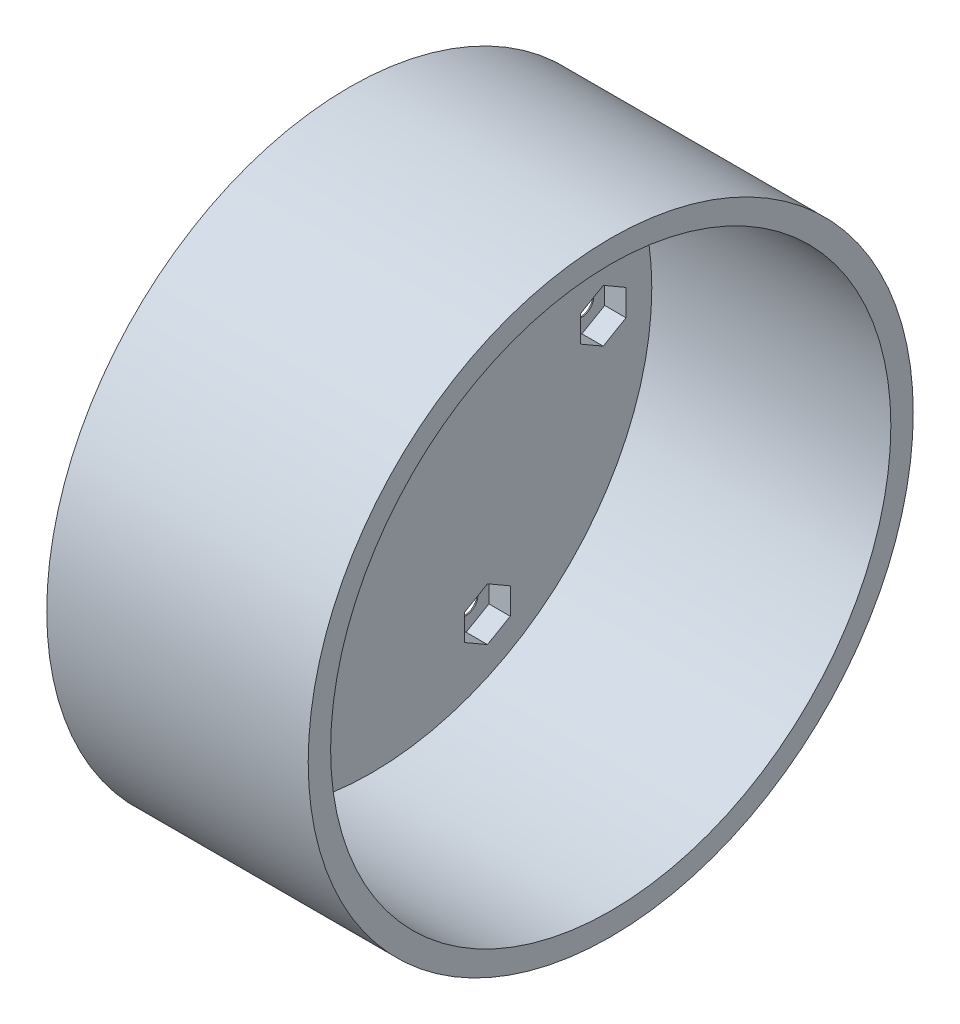
SolidWorks part; units mm, degrees
ref_plane "Front Plane" through (0, 0, 0) normal (0, 0, 1) x (1, 0, 0)
ref_plane "Top Plane" through (0, 0, 0) normal (0, 1, 0) x (1, 0, 0)
ref_plane "Right Plane" through (0, 0, 0) normal (1, 0, 0) x (0, 0, -1)
sketch "Sketch1" plane through (0, 0, 0) normal (0, 0, 1) x (1, 0, 0)
  line L0 (0, 0) -> (84.887, 0) construction
  line L7 (0, 0) -> (0, 40.5)
  line L8 (0, 40.5) -> (35, 40.5)
  line L9 (35, 40.5) -> (35, 37.5)
  line L10 (35, 37.5) -> (3, 37.5)
  line L11 (3, 37.5) -> (3, 0)
  line L12 (3, 0) -> (0, 0)
  dimension "D1" = 35
  dimension "D2" = 3
  dimension "D3" = 75
revolve "Revolve1" add sketch "Sketch1" angle 360 about L0
sketch "Sketch2" plane through (3, 0, 0) normal (1, 0, 0) x (0, 0, -1)
  circle A0 centre (0, 0) radius 31 construction
  circle A1 centre (-31, 0) radius 1.5875
  circle A2 centre (-15.5, 26.8468) radius 1.5875
  circle A3 centre (15.5, 26.8468) radius 1.5875
  circle A4 centre (31, 0) radius 1.5875
  circle A5 centre (15.5, -26.8468) radius 1.5875
  circle A6 centre (-15.5, -26.8468) radius 1.5875
  point P5 (5.5788, 21.1188)
  point P6 (0, 0)
  point P18 (0, 0)
  dimension "D1" = 62
  dimension "D2" = 3.175
  dimension "D3" = 6
extrude "Cut-Extrude1" cut sketch "Sketch2" against normal up to next
sketch "Sketch3" plane through (3, 0, 0) normal (1, 0, 0) x (0, 0, -1)
  line L0 (0, 0) -> (15.5, 26.8468) construction
  line L1 (18.55, 25.0859) -> (18.55, 28.6077)
  line L2 (18.55, 28.6077) -> (15.5, 30.3686)
  line L3 (15.5, 30.3686) -> (12.45, 28.6077)
  line L4 (12.45, 28.6077) -> (12.45, 25.0859)
  line L5 (12.45, 25.0859) -> (15.5, 23.325)
  line L6 (15.5, 23.325) -> (18.55, 25.0859)
  circle A0 centre (15.5, 26.8468) radius 3.05 construction
  dimension "D1" = 6.1
extrude "Cut-Extrude2" cut sketch "Sketch3" against normal blind 2.8575
pattern_circular "CirPattern1" count 6 over 360 about axis through (0, 0, 0) along (1, 0, 0) of "Cut-Extrude2"
sketch "Sketch4" plane through (3, 0, 0) normal (1, 0, 0) x (0, 0, -1)
  circle A0 centre (0, 0) radius 3
  dimension "D1" = 6
extrude "Cut-Extrude3" cut sketch "Sketch4" against normal up to next
